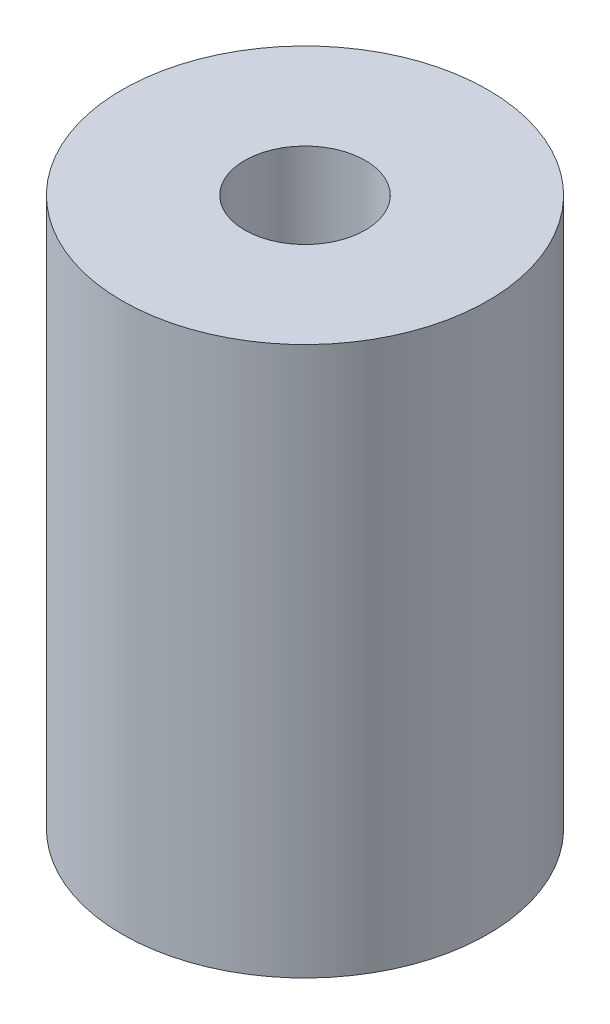
SolidWorks part; units mm, degrees
ref_plane "Спереди" through (0, 0, 0) normal (0, 0, 1) x (1, 0, 0)
ref_plane "Сверху" through (0, 0, 0) normal (0, 1, 0) x (1, 0, 0)
ref_plane "Справа" through (0, 0, 0) normal (1, 0, 0) x (0, 0, -1)
sketch "Эскиз1" plane through (0, 0, 0) normal (0, 1, 0) x (1, 0, 0)
  circle A0 centre (0, 0) radius 5
  circle A1 centre (0, 0) radius 1.65
  dimension "D1" = 10
  dimension "D2" = 3.3
extrude "Бобышка-Вытянуть1" add sketch "Эскиз1" along normal blind 15
